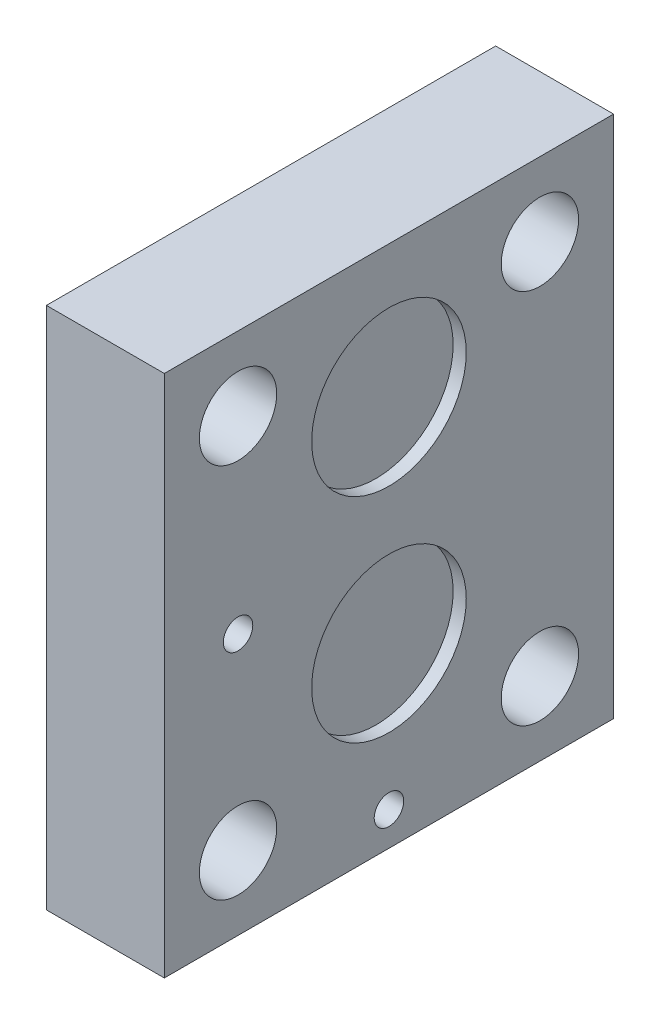
SolidWorks part; units mm, degrees
ref_plane "Front Plane" through (0, 0, 0) normal (1, 0, 0) x (0, 1, 0)
ref_plane "Top Plane" through (0, 0, 0) normal (0, 0, 1) x (0, 1, 0)
ref_plane "Right Plane" through (0, 0, 0) normal (0, 1, 0) x (-1, 0, 0)
sketch "Sketch1" plane through (0, 0, 0) normal (1, 0, 0) x (0, 1, 0)
  line L1 (0, 0) -> (112.776, 0)
  line L2 (0, 0) -> (0, 96.774)
  line L3 (0, 96.774) -> (112.776, 96.774)
  line L4 (112.776, 0) -> (112.776, 96.774)
extrude "Boss-Extrude1" add sketch "Sketch1" along normal blind 25.4
sketch "Sketch2" plane through (0, 0, 0) normal (1, 0, 0) x (0, 1, 0)
  circle A0 centre (15.875, 15.875) radius 8.3344
extrude "Cut-Extrude2" cut sketch "Sketch2" along normal through all
sketch "Sketch3" plane through (0, 0, 0) normal (1, 0, 0) x (0, 1, 0)
  circle A0 centre (96.901, 15.875) radius 8.3344
  circle A1 centre (15.875, 80.899) radius 8.3344
  circle A2 centre (96.901, 80.899) radius 8.3344
extrude "Cut-Extrude4" cut sketch "Sketch3" along normal through all
sketch "Sketch4" plane through (0, 0, 0) normal (1, 0, 0) x (0, 1, 0)
  circle A0 centre (105.537, 48.387) radius 3.5719
extrude "Cut-Extrude6" cut sketch "Sketch4" along normal blind 7.874
sketch "Sketch5" plane through (0, 0, 0) normal (1, 0, 0) x (0, 1, 0)
  circle A0 centre (56.515, 15.875) radius 3.5719
extrude "Cut-Extrude8" cut sketch "Sketch5" along normal blind 7.874
sketch "Sketch6" plane through (0, 0, 0) normal (1, 0, 0) x (0, 1, 0)
  circle A0 centre (7.239, 48.387) radius 3.175
extrude "Cut-Extrude10" cut sketch "Sketch6" against normal blind 7.874 from offset 25.4
sketch "Sketch7" plane through (0, 0, 0) normal (1, 0, 0) x (0, 1, 0)
  circle A0 centre (56.261, 80.899) radius 3.175
extrude "Cut-Extrude12" cut sketch "Sketch7" against normal blind 7.874 from offset 25.4
sketch "Sketch8" plane through (0, 0, 0) normal (1, 0, 0) x (0, 1, 0)
  circle A0 centre (38.227, 48.387) radius 16.6497
extrude "Cut-Extrude14" cut sketch "Sketch8" against normal blind 2.8194 from offset 25.4
sketch "Sketch9" plane through (0, 0, 0) normal (1, 0, 0) x (0, 1, 0)
  circle A0 centre (84.201, 48.387) radius 16.6497
extrude "Cut-Extrude15" cut sketch "Sketch9" against normal blind 2.8194 from offset 25.4
